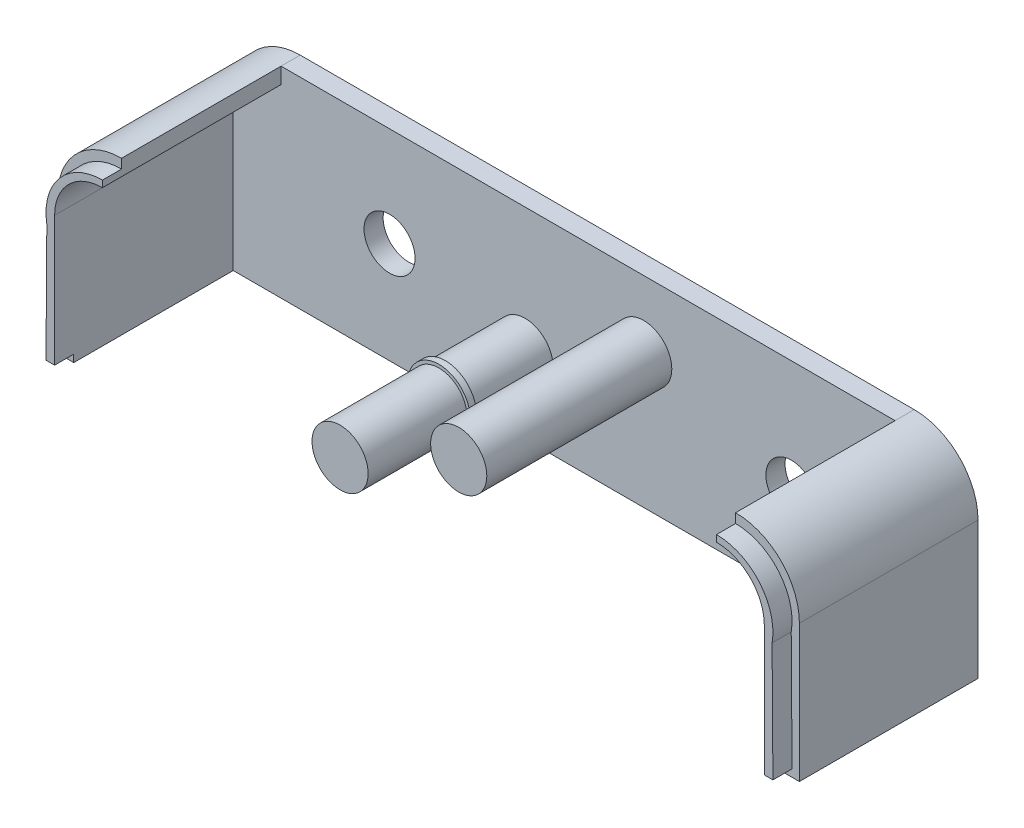
SolidWorks part; units mm, degrees
ref_plane "Front Plane" through (0, 0, 0) normal (0, 0, 1) x (1, 0, 0)
ref_plane "Top Plane" through (0, 0, 0) normal (0, 1, 0) x (1, 0, 0)
ref_plane "Right Plane" through (0, 0, 0) normal (1, 0, 0) x (0, 0, -1)
sketch "Sketch1" plane through (0, 0, 0) normal (0, 0, 1) x (1, 0, 0)
  line L0 (58.125, -1.75) -> (-58.125, -1.75) construction
  line L1 (-48.125, 15.75) -> (48.125, 15.75)
  line L2 (-58.125, 5.75) -> (-58.125, -15.75)
  line L3 (-58.125, -15.75) -> (58.125, -15.75)
  line L4 (58.125, 5.75) -> (58.125, -15.75)
  line L5 (-58.125, 15.75) -> (58.125, -15.75) construction
  line L6 (-58.125, -15.75) -> (58.125, 15.75) construction
  line L7 (31.875, 15.75) -> (31.875, -15.75) construction
  line L8 (-31.125, -15.75) -> (-31.125, 15.75) construction
  line L9 (-58.125, 0.15) -> (58.125, 0.15) construction
  arc A0 (48.125, 15.75) -> (58.125, 5.75) centre (48.125, 5.75) cw
  arc A1 (-48.125, 15.75) -> (-58.125, 5.75) centre (-48.125, 5.75) ccw
  circle A2 centre (31.875, -1.75) radius 4
  circle A3 centre (-31.125, 0.15) radius 4
  point P0 (0, 0)
  dimension "D3" = 10
  dimension "D6" = 8
  dimension "D8" = 8
  dimension "D1" = 116.25
  dimension "D2" = 31.5
  dimension "D4" = 14
  dimension "D5" = 26.25
  dimension "D7" = 15.9
  dimension "D9" = 27
extrude "Boss-Extrude2" add sketch "Sketch1" along normal blind 3
sketch "Sketch2" plane through (0, 0, 3) normal (0, 0, 1) x (1, 0, 0)
  line L0 (-17.875, 15.75) -> (-17.875, -15.75) construction
  line L1 (48.125, 15.75) -> (-48.125, 15.75) construction
  line L2 (-58.125, -15.75) -> (58.125, -15.75) construction
  line L3 (21.625, 15.75) -> (21.625, -15.75) construction
  line L4 (-58.125, 5.25) -> (58.125, 5.25) construction
  line L5 (-58.125, 5.75) -> (-58.125, -15.75) construction
  line L6 (58.125, -15.75) -> (58.125, 5.75) construction
  line L7 (8.725, 15.75) -> (8.725, -15.75) construction
  line L8 (-9.875, 15.75) -> (-9.875, -15.75) construction
  line L9 (-58.125, -3.75) -> (58.125, -3.75) construction
  line L10 (0.575, 5.25) -> (0.575, -15.75) construction
  line L11 (-18.025, -3.75) -> (-18.025, -15.75) construction
  line L26 (55.625, -15.75) -> (55.625, 5.75)
  line L27 (55.625, -15.75) -> (55.625, 5.75)
  line L28 (-55.625, -15.75) -> (-58.125, -15.75)
  line L29 (-55.625, 5.75) -> (-55.625, -15.75)
  line L30 (-55.625, 5.75) -> (-55.625, -15.75)
  line L31 (-58.125, -15.75) -> (-58.125, 5.25)
  line L32 (-48.125, 13.25) -> (-48.125, 15.75)
  line L33 (55.625, -15.75) -> (58.125, -15.75)
  line L34 (58.125, -15.75) -> (58.125, 5.25)
  line L35 (48.125, 13.25) -> (48.125, 15.75)
  circle A0 centre (-31.125, 0.15) radius 13.25 construction
  circle A1 centre (31.875, -1.75) radius 10.25 construction
  circle A2 centre (8.725, 5.25) radius 18 construction
  circle A3 centre (8.725, 5.25) radius 4.4
  circle A4 centre (8.725, 5.25) radius 8.15 construction
  circle A5 centre (-9.875, -3.75) radius 8.15 construction
  circle A6 centre (-9.875, -3.75) radius 4.4
  arc A10 (58.125, 5.75) -> (48.125, 15.75) centre (48.125, 5.75) ccw
  arc A11 (58.125, 5.75) -> (48.125, 15.75) centre (48.125, 5.75) ccw
  arc A13 (-48.125, 15.75) -> (-58.125, 5.75) centre (-48.125, 5.75) ccw
  arc A14 (-48.125, 15.75) -> (-58.125, 5.75) centre (-48.125, 5.75) ccw
  arc A28 (55.625, 5.75) -> (48.125, 13.25) centre (48.125, 5.75) ccw
  arc A29 (55.625, 5.75) -> (48.125, 13.25) centre (48.125, 5.75) ccw
  arc A32 (-48.125, 13.25) -> (-55.625, 5.75) centre (-48.125, 5.75) ccw
  arc A33 (-48.125, 13.25) -> (-55.625, 5.75) centre (-48.125, 5.75) ccw
  line M2 (58.125, -15.75) -> (58.125, 5.75)
  arc M3 (58.125, 5.75) -> (48.125, 15.75) centre (48.125, 5.75) ccw
  arc M5 (-48.125, 15.75) -> (-58.125, 5.75) centre (-48.125, 5.75) ccw
  line M6 (-58.125, 5.75) -> (-58.125, -15.75)
  line M7 (-58.125, -15.75) -> (58.125, -15.75)
  dimension "D1" = 26.5
  dimension "D2" = 20.5
  dimension "D6" = 8.8
  dimension "D8" = 10.45
  dimension "D9" = 8.8
  dimension "D10" = 18.45
  dimension "D7" = 31.5
  dimension "D11" = 12
  dimension "16" = 16.3
  dimension "D12" = 16.3
  dimension "D13" = 36
  dimension "D14" = 8
  dimension "D16" = 2.5
  dimension "D3" = 39.5
  dimension "D4" = 12.9
  dimension "D15" = 0.15
  dimension "D20" = 21
  dimension "D17" = 2.5
  dimension "D18" = 0
  dimension "D19" = 0
other "AlignGroup1"
other "AlignGroup2"
other "AlignGroup3"
other "AlignGroup4"
other "AlignGroup5"
extrude "Boss-Extrude3" add sketch "Sketch2" along normal blind 25 contours A3 | A6 | A29 L27 L35 M7 M2 M3 | A33 L32 L30 M5 M6 M7
sketch "Sketch5" plane through (0, 0, 28) normal (0, 0, 1) x (1, 0, 0)
  line L4 (-56.8469, 3.9347) -> (-56.975, -14.6)
  line L5 (0, 15.75) -> (0, -15.75) construction
  line L6 (48.125, 15.75) -> (-48.125, 15.75) construction
  line L7 (-55.625, -15.75) -> (55.625, -15.75) construction
  line L8 (-55.625, -14.6) -> (-56.975, -14.6)
  line L9 (-58.125, -15.75) -> (-55.625, -15.75) construction
  line L16 (55.625, -14.6) -> (55.625, 5.75)
  line L17 (48.125, 13.25) -> (48.125, 14.2852)
  line L18 (55.625, -14.6) -> (56.975, -14.6)
  line L19 (56.8469, 3.9347) -> (56.975, -14.6)
  line L28 (-48.125, 13.25) -> (-48.125, 15.75)
  line L29 (-58.125, 5.75) -> (-58.125, -15.75)
  line L30 (-58.125, -15.75) -> (-55.625, -15.75)
  line L31 (-55.625, -15.75) -> (-55.625, 5.75)
  line L32 (-48.125, 13.25) -> (-48.125, 14.2852)
  line L35 (-55.625, -14.6) -> (-55.625, 5.75)
  arc A2 (-48.125, 14.2852) -> (-56.8469, 3.9347) centre (-48.125, 5.4352) ccw
  arc A3 (48.125, 13.25) -> (55.625, 5.75) centre (48.125, 5.75) cw
  arc A4 (48.125, 14.2852) -> (56.8469, 3.9347) centre (48.125, 5.4352) cw
  arc A14 (-48.125, 13.25) -> (-55.625, 5.75) centre (-48.125, 5.75) ccw
  arc A15 (-48.125, 15.75) -> (-58.125, 5.75) centre (-48.125, 5.75) ccw
  arc A16 (-48.125, 13.25) -> (-55.625, 5.75) centre (-48.125, 5.75) ccw
  dimension "D1" = 1.35
  dimension "D3" = 0.3148
  dimension "D4" = 8.85
  dimension "D2" = 1.15
  dimension "D6" = 18.5352
  dimension "D5" = 0
sketch "Sketch10" plane through (0, 0, 28) normal (0, 0, 1) x (1, 0, 0)
  circle A1 centre (8.725, 5.25) radius 4.4
  circle A2 centre (8.725, 5.25) radius 4.4
  circle A3 centre (-9.875, -3.75) radius 4.4
  circle A4 centre (-9.875, -3.75) radius 4.4
  dimension "D1" = 0
  dimension "D2" = 0
extrude "Cut-Extrude3" cut sketch "Sketch10" against normal blind 1
extrude "Boss-Extrude5" add sketch "Sketch5" along normal blind 3
sketch "Sketch12" plane through (0, 0, 27) normal (0, 0, 1) x (1, 0, 0)
  circle A0 centre (-9.875, -3.75) radius 4.4 construction
  circle A1 centre (8.725, 5.25) radius 4.4 construction
  circle A2 centre (-9.875, -3.75) radius 4.4
  circle A3 centre (8.725, 5.25) radius 4.4
extrude "Boss-Extrude6" add sketch "Sketch12" along normal blind 5
ref_plane "Plane2" through (0, 0, 15.5) normal (0, 0, 1) x (1, 0, 0)
sketch "Sketch14" plane through (0, 0, 15.5) normal (0, 0, 1) x (1, 0, 0)
  circle A2 centre (-9.875, -3.75) radius 4.9
  circle A3 centre (-9.875, -3.75) radius 4.9
  dimension "D1" = 0.5
extrude "Boss-Extrude7" add sketch "Sketch14" along normal blind 1
